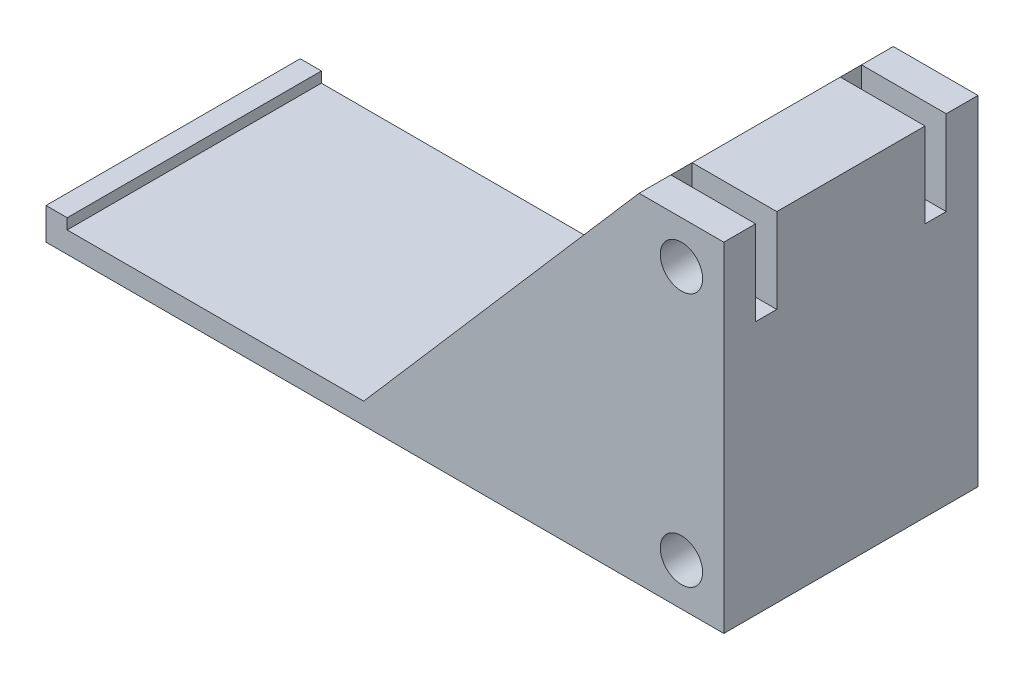
SolidWorks part; units mm, degrees
ref_plane "Front Plane" through (0, 0, 0) normal (0, 0, 1) x (1, 0, 0)
ref_plane "Top Plane" through (0, 0, 0) normal (0, 1, 0) x (1, 0, 0)
ref_plane "Right Plane" through (0, 0, 0) normal (1, 0, 0) x (0, 0, -1)
sketch "Sketch1" plane through (0, 0, 0) normal (0, 0, 1) x (1, 0, 0)
  line L0 (0, 0) -> (-25.4, 0)
  line L1 (0, 0) -> (0, 152.4)
  line L2 (-25.4, 0) -> (-25.4, 152.4)
  line L3 (0, 152.4) -> (-25.4, 152.4)
  line L4 (-25.4, 0) -> (-25.4, 25.4)
  line L5 (-25.4, 0) -> (-406.4, 0)
  line L6 (-25.4, 25.4) -> (-406.4, 25.4)
  line L7 (-406.4, 0) -> (-406.4, 25.4)
  line L8 (-25.4, 177.8) -> (-25.4, -25.4)
  line L9 (-25.4, 177.8) -> (25.4, 177.8)
  line L10 (-25.4, -25.4) -> (25.4, -25.4)
  line L11 (25.4, 177.8) -> (25.4, -25.4)
  point P0 (0, 0)
  dimension "D1" = 25.4
  dimension "D2" = 152.4
  dimension "D3" = 25.4
  dimension "D4" = 381
  dimension "D5" = 50.8
  dimension "D6" = 25.4
  dimension "D7" = 25.4
extrude "Boss-Extrude1" add sketch "Sketch1" along normal mid plane 152.4 contours L7 L5 L2 L6 | L1 L3 L2 L0 | L11 L9 L8 L3 L1 L0 L10
sketch "Sketch2" plane through (0, 0, 76.2) normal (0, 0, 1) x (1, 0, 0)
  circle A0 centre (0, 0) radius 12.7
  circle A1 centre (0, 152.4) radius 12.7
  dimension "D1" = 25.4
  dimension "D2" = 25.4
extrude "Cut-Extrude1" cut sketch "Sketch2" against normal through all both and the other way through all
sketch "Sketch3" plane through (0, 177.8, 0) normal (0, 1, 0) x (1, 0, 0)
  line L0 (-25.4, -76.2) -> (-25.4, -50.8)
  line L1 (-25.4, -76.2) -> (-25.4, 76.2) construction
  line L2 (-25.4, -50.8) -> (25.4, -50.8)
  line L3 (25.4, -76.2) -> (25.4, 76.2) construction
  dimension "D1" = 25.4
ref_plane "Plane1" through (0, 0, 50.8) normal (0, 0, 1) x (1, 0, 0)
sketch "Sketch4" plane through (0, 0, 50.8) normal (0, 0, 1) x (1, 0, 0)
  line L0 (-25.4, 177.8) -> (-25.4, 127)
  line L1 (-25.4, 0) -> (-25.4, 152.4) construction
  line L2 (-25.4, 127) -> (25.4, 127)
  line L3 (25.4, 177.8) -> (25.4, -25.4) construction
  line L4 (25.4, 127) -> (25.4, 177.8)
  line L5 (25.4, 177.8) -> (-25.4, 177.8)
  dimension "D1" = 50.8
extrude "Cut-Extrude2" cut sketch "Sketch4" against normal mid plane 12.7
mirror "Mirror1" about plane through (0, 0, 0) normal (0, 0, 1) of "Cut-Extrude2"
sketch "Sketch5" plane through (0, 0, 0) normal (0, 0, 1) x (1, 0, 0)
  line L1 (-406.4, 25.4) -> (-25.4, 25.4)
  line L2 (-406.4, 25.4) -> (-406.4, 0)
  line L3 (-406.4, 0) -> (-25.4, 0)
  line L4 (-25.4, 25.4) -> (-25.4, 0)
extrude "Cut-Extrude3" cut sketch "Sketch5" against normal through all both and the other way through all
sketch "Sketch6" plane through (0, 0, 0) normal (0, 0, 1) x (1, 0, 0)
  line L0 (-25.4, -25.4) -> (-381, -25.4)
  line L1 (-381, -25.4) -> (-381, -6.35)
  line L2 (-381, -6.35) -> (-368.3, -6.35)
  line L3 (-368.3, -6.35) -> (-368.3, -12.7)
  line L4 (-368.3, -12.7) -> (-190.5, -12.7)
  line L5 (-190.5, -12.7) -> (-25.4, 177.8)
  line L6 (-25.4, -25.4) -> (-25.4, 177.8) construction
  line L7 (-25.4, 177.8) -> (-25.4, -25.4)
  point P3 (0, 0)
  dimension "D1" = 19.05
  dimension "D2" = 6.35
  dimension "D3" = 12.7
  dimension "D4" = 355.6
  dimension "D5" = 177.8
extrude "Boss-Extrude2" add sketch "Sketch6" along normal mid plane 152.4
